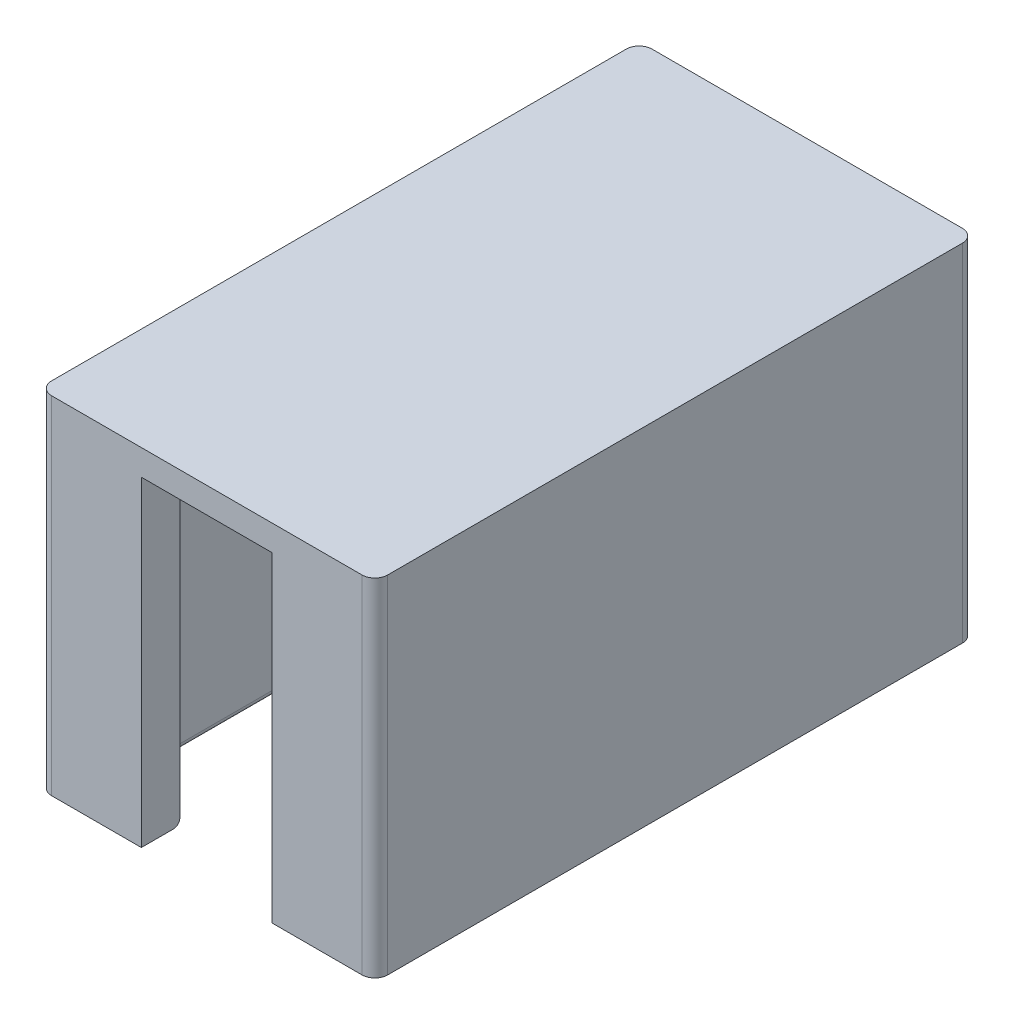
SolidWorks part; units mm, degrees
ref_plane "Front Plane" through (0, 0, 0) normal (0, 0, 1) x (1, 0, 0)
ref_plane "Top Plane" through (0, 0, 0) normal (0, 1, 0) x (1, 0, 0)
ref_plane "Right Plane" through (0, 0, 0) normal (1, 0, 0) x (0, 0, -1)
sketch "Sketch1" plane through (0, 0, 0) normal (0, 1, 0) x (1, 0, 0)
  line L5 (0, 0) -> (26.2, 0)
  line L6 (0, 0) -> (0, 46.8)
  line L7 (0, 46.8) -> (26.2, 46.8)
  line L8 (26.2, 0) -> (26.2, 46.8)
  line L9 (3, 3) -> (23.2, 3)
  line L10 (3, 3) -> (3, 43.8)
  line L11 (3, 43.8) -> (23.2, 43.8)
  line L12 (23.2, 3) -> (23.2, 43.8)
  dimension "D1" = 20.2
  dimension "D2" = 40.8
  dimension "D3" = 3
  dimension "D4" = 3
  dimension "D5" = 3
  dimension "D6" = 3
extrude "Boss-Extrude1" add sketch "Sketch1" along normal blind 25
sketch "Sketch3" plane through (0, 0, 0) normal (0, 0, 1) x (1, 0, 0)
  line L0 (0, 0) -> (26.2, 0) construction
  line L1 (8, 0) -> (18.2, 0)
  line L2 (8, 0) -> (8, 25)
  line L3 (8, 25) -> (18.2, 25)
  line L4 (18.2, 0) -> (18.2, 25)
  line L5 (0, 25) -> (26.2, 25) construction
  line L6 (0, 25) -> (0, 0) construction
  line L7 (26.2, 25) -> (26.2, 0) construction
  dimension "D1" = 8
  dimension "D2" = 8
extrude "Cut-Extrude1" cut sketch "Sketch3" against normal blind 10 contours L2 L1 L4 L3
fillet "Fillet1" radius 0.5 10 edges at (5.5, 25, -3) (3, 25, -23.4) (13.1, 25, -43.8) (20.7, 25, -3) (23.2, 25, -23.4) (5.5, 0, -3) (3, 0, -23.4) (13.1, 0, -43.8) (23.2, 0, -23.4) (20.7, 0, -3)
sketch "Sketch4" plane through (0, 25, 0) normal (0, 1, 0) x (1, 0, 0)
  line L1 (0, 0) -> (26.2, 0)
  line L2 (0, 0) -> (0, 46.8)
  line L3 (0, 46.8) -> (26.2, 46.8)
  line L4 (26.2, 0) -> (26.2, 46.8)
extrude "Boss-Extrude2" add sketch "Sketch4" along normal blind 2
fillet "Fillet2" radius 1 4 edges at (26.2, 13.5, -46.8) (0, 13.5, -46.8) (26.2, 13.5, 0) (0, 13.5, 0)
